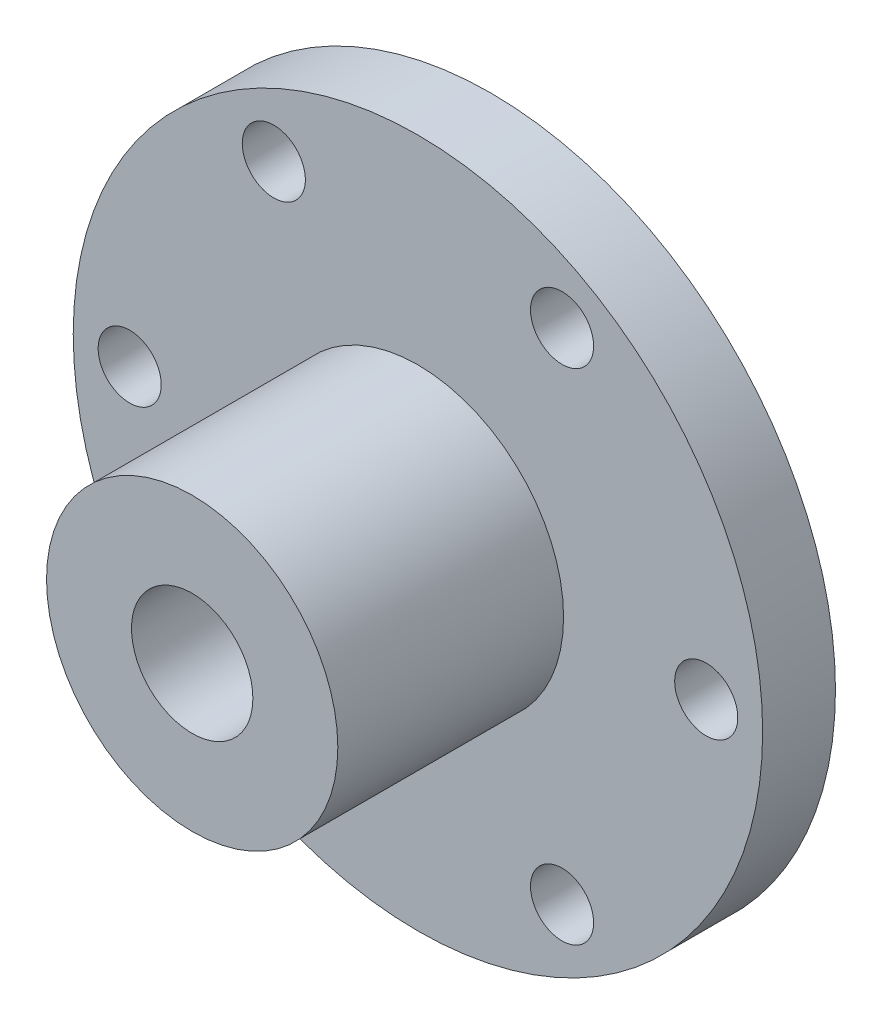
SolidWorks part; units mm, degrees
material "6061 Alloy"
ref_plane "Front Plane" through (0, 0, 0) normal (0, 0, 1) x (1, 0, 0)
ref_plane "Top Plane" through (0, 0, 0) normal (0, 1, 0) x (1, 0, 0)
ref_plane "Right Plane" through (0, 0, 0) normal (1, 0, 0) x (0, 0, -1)
sketch "Sketch1" plane through (0, 0, 0) normal (0, 1, 0) x (1, 0, 0)
  line L0 (0, 0) -> (0, 24.6) construction
  line L1 (-5, 24.6) -> (-28.4, 24.6)
  line L2 (-28.4, 24.6) -> (-28.4, 18.6)
  line L3 (-28.4, 18.6) -> (-12, 18.6)
  line L4 (-12, 18.6) -> (-12, 0)
  line L5 (-12, 0) -> (-5, 0)
  line L6 (-5, 0) -> (-5, 24.6)
  dimension "D1" = 5
  dimension "D2" = 24.6
  dimension "D3" = 6
  dimension "D4" = 12
  dimension "D5" = 28.4
revolve "Revolve1" add sketch "Sketch1" angle 360 about L0
sketch "Sketch2" plane through (0, 0, -24.6) normal (0, 0, -1) x (-1, 0, 0)
  line L0 (-23.75, 0) -> (0, 0) construction
  circle A0 centre (-23.75, 0) radius 2.6
  circle A1 centre (-11.875, 20.5681) radius 2.6
  circle A2 centre (11.875, 20.5681) radius 2.6
  circle A3 centre (23.75, 0) radius 2.6
  circle A4 centre (11.875, -20.5681) radius 2.6
  circle A5 centre (-11.875, -20.5681) radius 2.6
  point P16 (0, 0)
  dimension "D1" = 5.2
  dimension "D2" = 23.75
  dimension "D3" = 6
extrude "Cut-Extrude1" cut sketch "Sketch2" against normal through all
sketch "Sketch3" plane through (0, 0, 0) normal (0, 1, 0) x (1, 0, 0)
  line L0 (-12, 0) -> (12, 0) construction
  circle A0 centre (0, 10.2) radius 2.75
  dimension "D2" = 5.5
  dimension "D1" = 10.2
extrude "Cut-Extrude2" cut sketch "Sketch3" against normal up to next
